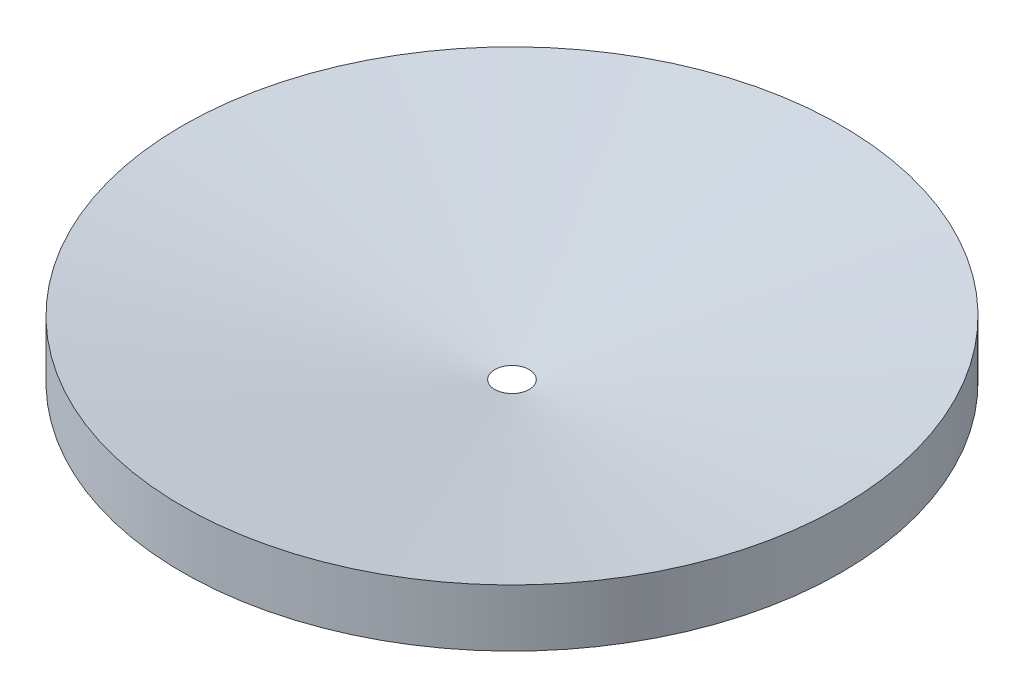
SolidWorks part; units mm, degrees
ref_plane "Front Plane" through (0, 0, 0) normal (0, 0, 1) x (1, 0, 0)
ref_plane "Top Plane" through (0, 0, 0) normal (0, 1, 0) x (1, 0, 0)
ref_plane "Right Plane" through (0, 0, 0) normal (1, 0, 0) x (0, 0, -1)
sketch "Sketch1" plane through (0, 0, 0) normal (0, 0, 1) x (1, 0, 0)
  line L0 (-57.5, 10) -> (57.5, 10) construction
  line L1 (57.5, 10) -> (3, 0.3902)
  line L2 (0, 10) -> (0, 0) construction
  line L3 (57.5, 10) -> (57.5, 0)
  line L4 (3, 0.3902) -> (5.8794, 0.3902)
  line L5 (5.8794, 0.3902) -> (56, 9.2278)
  line L6 (57.5, 0) -> (56, 0)
  line L7 (56, 0) -> (56, 9.2278)
  point P2 (0, 10)
  point P10 (-61.2576, 21.5423)
  point P12 (-60.9533, 40.3392)
  dimension "D1" = 115
  dimension "D2" = 10
  dimension "D3" = 3
  dimension "D4" = 10
  dimension "D5" = 10
  dimension "D6" = 0.5
  dimension "D7" = 1.5
revolve "Revolve1" add sketch "Sketch1" angle 360 about L2
